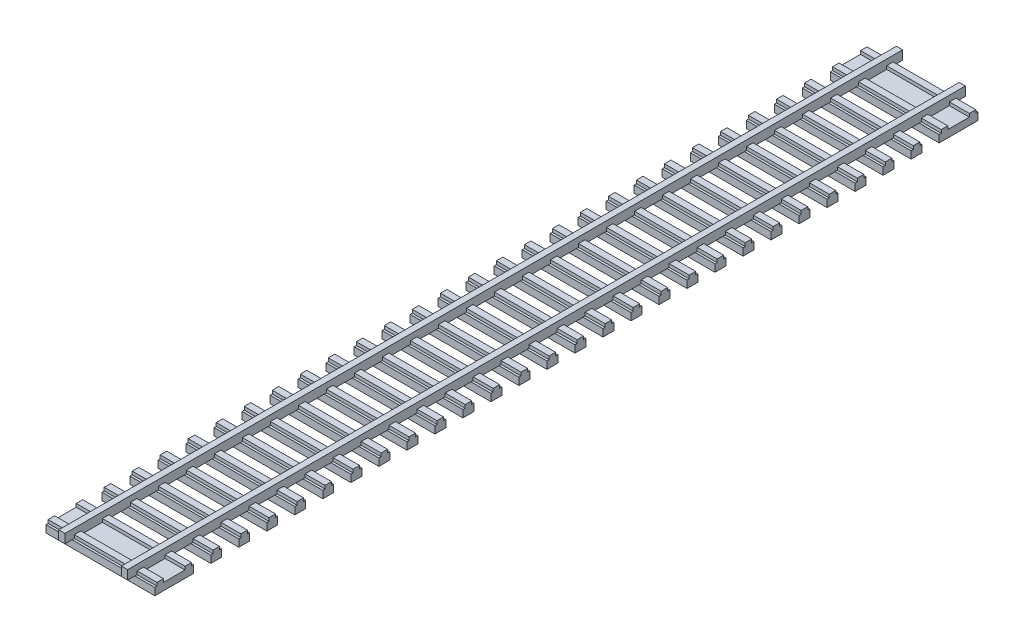
SolidWorks part; units mm, degrees
ref_plane "Спереди" through (0, 0, 0) normal (0, 0, 1) x (1, 0, 0)
ref_plane "Сверху" through (0, 0, 0) normal (0, 1, 0) x (1, 0, 0)
ref_plane "Справа" through (0, 0, 0) normal (1, 0, 0) x (0, 0, -1)
sketch "Эскиз1" plane through (0, 0, 0) normal (0, 0, 1) x (1, 0, 0)
  line L0 (8.645, 0) -> (8.645, 2.5) construction
  line L1 (7.79, 0) -> (9.5, 0)
  line L2 (7.79, 0) -> (7.79, 2.5)
  line L3 (7.79, 2.5) -> (9.5, 2.5)
  line L4 (9.5, 0) -> (9.5, 2.5)
  line L5 (0, 0) -> (0, 50000) construction
  line L6 (-8.645, 0) -> (-8.645, 2.5) construction
  line L7 (-9.5, 0) -> (-9.5, 2.5)
  line L8 (-7.79, 2.5) -> (-9.5, 2.5)
  line L9 (-7.79, 0) -> (-7.79, 2.5)
  line L10 (-7.79, 0) -> (-9.5, 0)
  point P15 (-7.79, 1.5675)
  dimension "D1" = 1.71
  dimension "D2" = 2.5
  dimension "D3" = 19
extrude "Бобышка-Вытянуть1" add sketch "Эскиз1" against normal mid plane 231 contours L3 L4 L1 L2
sketch "Эскиз2" plane through (0, 0, 0) normal (1, 0, 0) x (0, 0, -1)
  line L0 (115.5, 0) -> (-115.5, 0) construction
  line L1 (-113.5, 0) -> (-110.5, 0)
  line L2 (-113.5, 0) -> (-113.5, -2)
  line L3 (-113.5, -2) -> (-110.5, -2)
  line L4 (-110.5, 0) -> (-110.5, -2)
  line L5 (-115.5, 0) -> (-115.5, 2.5) construction
  line L7 (-112.9, 0) -> (-111.1, 0)
  line L8 (-112.9, 0) -> (-112.9, 0.9)
  line L9 (-112.9, 0.9) -> (-111.1, 0.9)
  line L10 (-111.1, 0) -> (-111.1, 0.9)
  line L11 (-112, 0.9) -> (-112, 0) construction
  line L12 (-112.9, 0.45) -> (-111.1, 0.45) construction
  point P8 (0, 0)
  point P114 (-112, 0.45)
  dimension "D1" = 2
  dimension "D2" = 2
  dimension "D3" = 3
  dimension "D4" = 2.9
  dimension "D5" = 1.8
extrude "Бобышка-Вытянуть2" add sketch "Эскиз2" along normal mid plane 30 contours L4 L1 L2 L3 | L1 L10 L9 L8
pattern_linear "Линейный массив1" count 30 spacing 7.7241 along (0, 0, -1) of "Бобышка-Вытянуть2"
sketch "Эскиз3" plane through (15, 0, 0) normal (1, 0, 0) x (0, 0, -1)
  line L0 (-105.7759, 0) -> (-105.7759, -2) construction
  line L1 (-110.5, 0) -> (-105.7759, 0)
  line L2 (-110.5, 0) -> (-110.5, -2)
  line L3 (-110.5, -2) -> (-105.7759, -2)
  line L4 (-105.7759, 0) -> (-105.7759, -2)
  line L5 (-108.1379, -2) -> (-108.1379, 0) construction
  line L6 (-110.5, -1) -> (-105.7759, -1) construction
  line L7 (-105.7759, -2) -> (-102.7759, -2) construction
  line L9 (105.7759, 0) -> (110.5, 0)
  line L10 (105.7759, 0) -> (105.7759, -2)
  line L11 (105.7759, -2) -> (110.5, -2)
  line L12 (110.5, 0) -> (110.5, -2)
  line L13 (108.1379, -2) -> (108.1379, 0) construction
  line L14 (105.7759, -1) -> (110.5, -1) construction
  point P92 (108.1379, -1)
  point P116 (-108.1379, -1)
extrude "Бобышка-Вытянуть3" add sketch "Эскиз3" against normal through all
